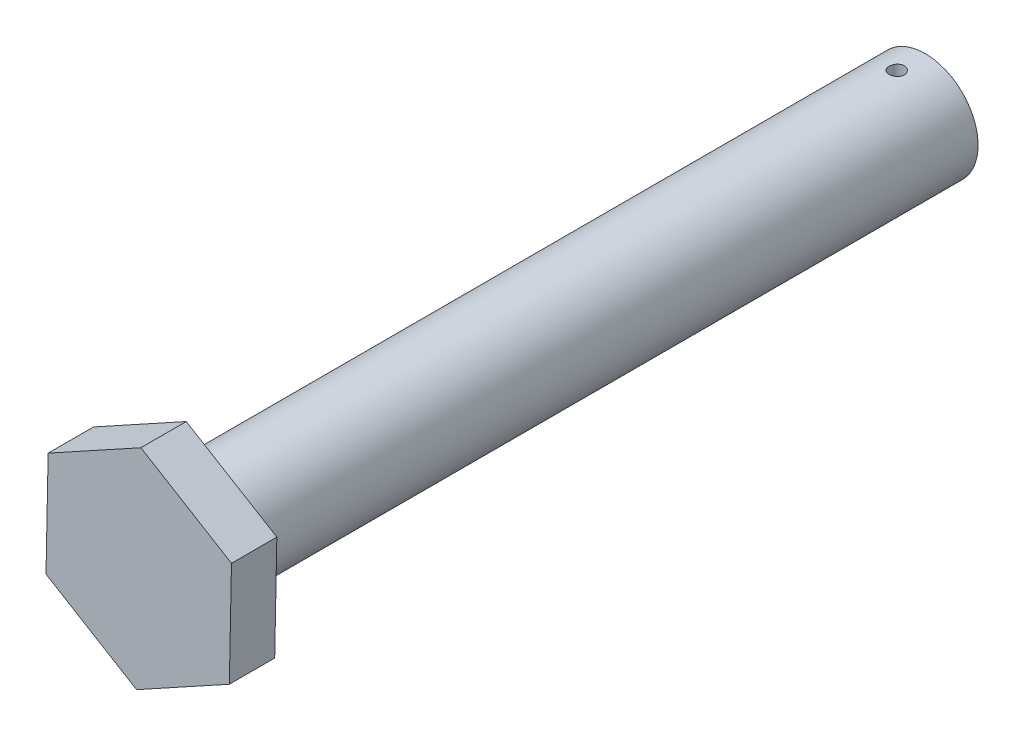
SolidWorks part; units mm, degrees
ref_plane "Front Plane" through (0, 0, 0) normal (0, 0, 1) x (1, 0, 0)
ref_plane "Top Plane" through (0, 0, 0) normal (0, 1, 0) x (1, 0, 0)
ref_plane "Right Plane" through (0, 0, 0) normal (1, 0, 0) x (0, 0, -1)
sketch "Sketch1" plane through (0, 0, 0) normal (0, 0, 1) x (1, 0, 0)
  circle A0 centre (0, 0) radius 3.5
  dimension "D1" = 7
extrude "Boss-Extrude1" add sketch "Sketch1" along normal blind 46
sketch "Sketch2" plane through (0, 0, 46) normal (0, 0, 1) x (1, 0, 0)
  line L1 (0.142, 6.9986) -> (-5.9899, 3.6223)
  line L2 (-5.9899, 3.6223) -> (-6.1319, -3.3763)
  line L3 (-6.1319, -3.3763) -> (-0.142, -6.9986)
  line L4 (-0.142, -6.9986) -> (5.9899, -3.6223)
  line L5 (5.9899, -3.6223) -> (6.1319, 3.3763)
  line L6 (6.1319, 3.3763) -> (0.142, 6.9986)
  circle A0 centre (0, 0) radius 6.0622 construction
  point P1 (4.8057, 2.9062)
extrude "Boss-Extrude2" add sketch "Sketch2" along normal blind 3
sketch "Sketch3" plane through (0, 0, 0) normal (0, 0, -1) x (-1, 0, 0)
  circle A0 centre (0, 0) radius 3.5
extrude "Boss-Extrude3" add sketch "Sketch3" along normal blind 3
sketch "Sketch4" plane through (0, 0, 0) normal (0, 1, 0) x (1, 0, 0)
  circle A0 centre (0, 1.1121) radius 0.5
  dimension "D1" = 1
extrude "Cut-Extrude2" cut sketch "Sketch4" along normal blind 13 and the other way blind 15
